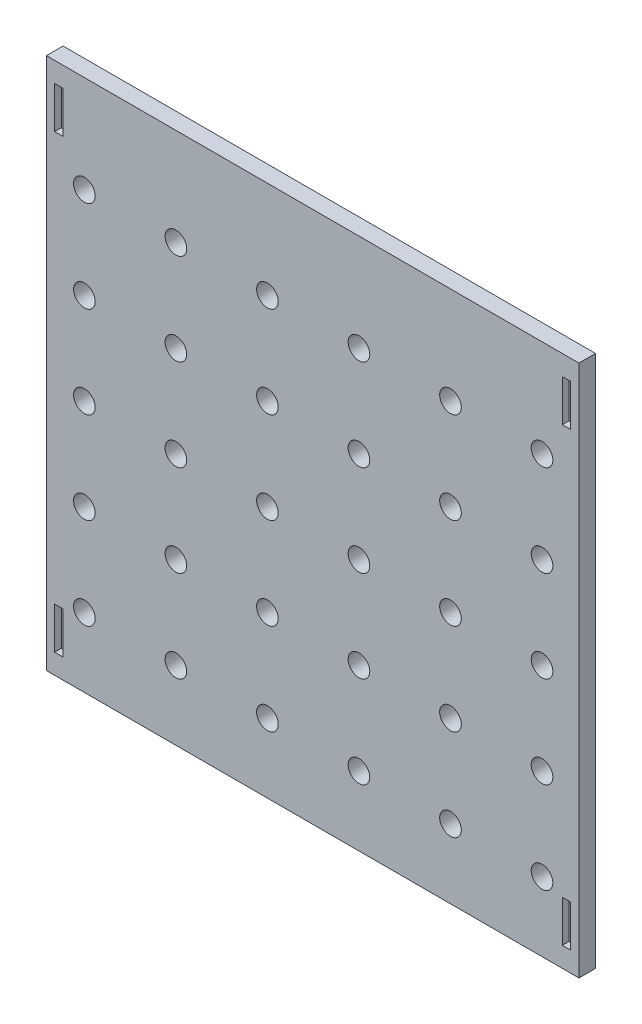
SolidWorks part; units mm, degrees
ref_plane "Alzado" through (0, 0, 0) normal (0, 0, 1) x (1, 0, 0)
ref_plane "Planta" through (0, 0, 0) normal (0, 1, 0) x (1, 0, 0)
ref_plane "Vista lateral" through (0, 0, 0) normal (1, 0, 0) x (0, 0, -1)
sketch "Croquis1" plane through (0, 0, 0) normal (0, 0, 1) x (1, 0, 0)
  line L1 (-320, 320) -> (320, 320)
  line L2 (-320, 320) -> (-320, -320)
  line L3 (-320, -320) -> (320, -320)
  line L4 (320, 320) -> (320, -320)
  line L5 (-320, 320) -> (320, -320) construction
  line L6 (-320, -320) -> (320, 320) construction
  point P0 (0, 0)
  dimension "D1" = 640
  dimension "D2" = 640
extrude "Saliente-Extruir1" add sketch "Croquis1" along normal blind 20
sketch "Croquis2" plane through (0, 0, 20) normal (0, 0, 1) x (1, 0, 0)
  line L1 (-310.1, 295.9817) -> (-300, 295.9817)
  line L2 (-310.1, 295.9817) -> (-310.1, 245.8817)
  line L3 (-310.1, 245.8817) -> (-300, 245.8817)
  line L4 (-300, 295.9817) -> (-300, 245.8817)
  line L6 (300, 295.9817) -> (300, 245.8817)
  line L7 (310.1, 245.8817) -> (300, 245.8817)
  line L8 (310.1, 295.9817) -> (310.1, 245.8817)
  line L9 (310.1, 295.9817) -> (300, 295.9817)
  dimension "D1" = 10.1
  dimension "D2" = 50.1
  dimension "D3" = 600
extrude "Cortar-Extruir1" cut sketch "Croquis2" against normal blind 8
mirror "Simetría1" about plane through (0, 0, 0) normal (0, 1, 0) of "Cortar-Extruir1"
sketch "Croquis3" plane through (0, 0, 20) normal (0, 0, 1) x (1, 0, 0)
  circle A0 centre (-274.3885, 203.2507) radius 13
  circle A1 centre (-164.3885, 203.2507) radius 13
  circle A2 centre (-54.3885, 203.2507) radius 13
  circle A3 centre (55.6115, 203.2507) radius 13
  circle A4 centre (165.6115, 203.2507) radius 13
  circle A5 centre (275.6115, 203.2507) radius 13
  circle A6 centre (-164.3885, 93.2507) radius 13
  circle A7 centre (-54.3885, 93.2507) radius 13
  circle A8 centre (55.6115, 93.2507) radius 13
  circle A9 centre (165.6115, 93.2507) radius 13
  circle A10 centre (275.6115, 93.2507) radius 13
  circle A11 centre (-164.3885, -16.7493) radius 13
  circle A12 centre (-54.3885, -16.7493) radius 13
  circle A13 centre (55.6115, -16.7493) radius 13
  circle A14 centre (165.6115, -16.7493) radius 13
  circle A15 centre (275.6115, -16.7493) radius 13
  circle A16 centre (-164.3885, -126.7493) radius 13
  circle A17 centre (-54.3885, -126.7493) radius 13
  circle A18 centre (55.6115, -126.7493) radius 13
  circle A19 centre (165.6115, -126.7493) radius 13
  circle A20 centre (275.6115, -126.7493) radius 13
  circle A21 centre (-164.3885, -236.7493) radius 13
  circle A22 centre (-54.3885, -236.7493) radius 13
  circle A23 centre (55.6115, -236.7493) radius 13
  circle A24 centre (165.6115, -236.7493) radius 13
  circle A25 centre (275.6115, -236.7493) radius 13
  circle A26 centre (-274.3885, 93.2507) radius 13
  circle A27 centre (-274.3885, -16.7493) radius 13
  circle A28 centre (-274.3885, -126.7493) radius 13
  circle A29 centre (-274.3885, -236.7493) radius 13
  dimension "D1" = 6
  dimension "D2" = 5
extrude "Cortar-Extruir2" cut sketch "Croquis3" against normal blind 48
